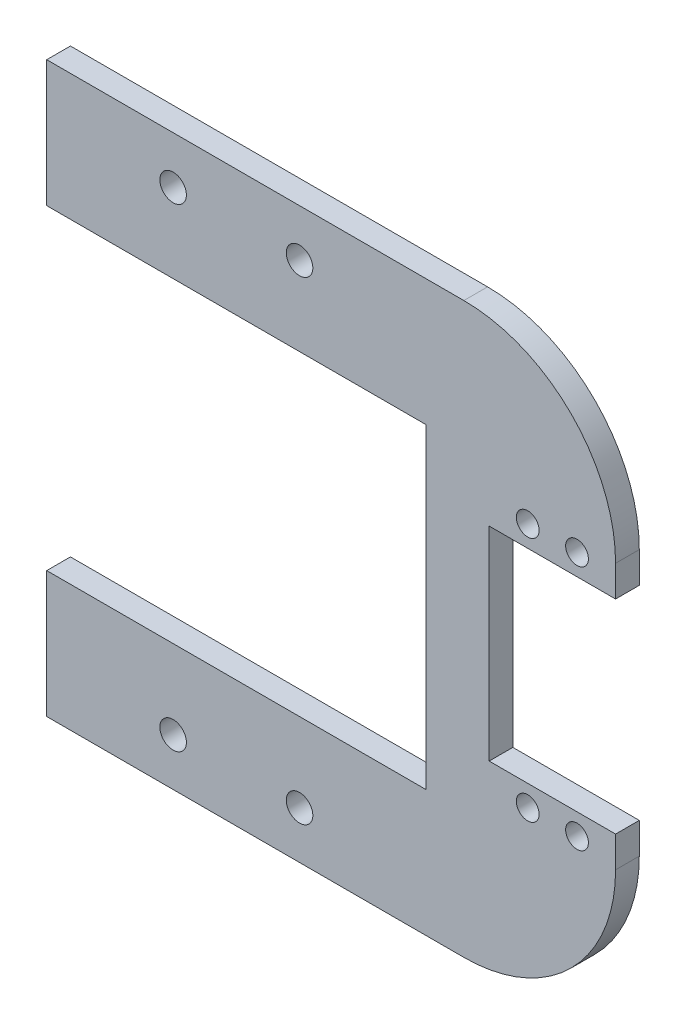
SolidWorks part; units mm, degrees
ref_plane "Front Plane" through (0, 0, 0) normal (0, 0, 1) x (1, 0, 0)
ref_plane "Top Plane" through (0, 0, 0) normal (0, 1, 0) x (1, 0, 0)
ref_plane "Right Plane" through (0, 0, 0) normal (1, 0, 0) x (0, 0, -1)
sketch "Sketch1" plane through (0, 0, 0) normal (0, 0, 1) x (1, 0, 0)
  line L0 (0, 0) -> (0, 63.5)
  line L1 (0, 63.5) -> (-76.2, 63.5)
  line L2 (-76.2, 63.5) -> (-76.2, 88.9)
  line L5 (38.1, 52.197) -> (12.7, 52.197)
  line L6 (12.7, 52.197) -> (12.7, 11.303)
  line L7 (12.7, 11.303) -> (38.1, 11.303)
  line L10 (-76.2, -25.4) -> (-76.2, 0)
  line L11 (-76.2, 0) -> (0, 0)
  line L12 (25.4, 52.197) -> (25.4, 56.4515) construction
  line L13 (25.4, 56.4515) -> (30.353, 56.4515) construction
  line L14 (25.4, 56.4515) -> (20.447, 56.4515) construction
  line L15 (25.4, 11.303) -> (25.4, 7.0485) construction
  line L16 (25.4, 7.0485) -> (20.447, 7.0485) construction
  line L17 (25.4, 7.0485) -> (30.353, 7.0485) construction
  line L18 (-50.8, 79.375) -> (-25.4, 79.375) construction
  line L27 (-25.4, 79.375) -> (-25.4, -15.875) construction
  line L28 (-25.4, -15.875) -> (-50.8, -15.875) construction
  line L29 (-76.2, 88.9) -> (7.62, 88.9)
  line L30 (38.1, 52.197) -> (38.1, 58.42)
  line L31 (38.1, 11.303) -> (38.1, 5.08)
  line L32 (-76.2, -25.4) -> (7.62, -25.4)
  circle A0 centre (20.447, 56.4515) radius 2.286
  circle A1 centre (30.353, 56.4515) radius 2.286
  circle A2 centre (20.447, 7.0485) radius 2.286
  circle A3 centre (30.353, 7.0485) radius 2.286
  circle A4 centre (-50.8, 79.375) radius 2.667
  circle A5 centre (-25.4, 79.375) radius 2.667
  circle A6 centre (-50.8, -15.875) radius 2.667
  circle A7 centre (-25.4, -15.875) radius 2.667
  arc A8 (7.62, 88.9) -> (38.1, 58.42) centre (7.62, 58.42) cw
  arc A9 (38.1, 5.08) -> (7.62, -25.4) centre (7.62, 5.08) cw
  point P25 (0, 0)
  point P26 (0, 0)
  point P27 (0, 0)
  point P32 (0, 0)
  dimension "D1" = 4.572
  dimension "D17" = 5.334
  dimension "D8" = 30.48
  dimension "D11" = 30.48
  dimension "D2" = 49.403
  dimension "D3" = 9.906
  dimension "D4" = 76.2
  dimension "D5" = 25.4
  dimension "D6" = 63.5
  dimension "D7" = 12.7
  dimension "D9" = 40.894
  dimension "D10" = 114.3
  dimension "D12" = 9.525
  dimension "D13" = 9.525
  dimension "D16" = 25.4
  dimension "D18" = 25.4
extrude "Boss-Extrude1" add sketch "Sketch1" along normal blind 4.7625
